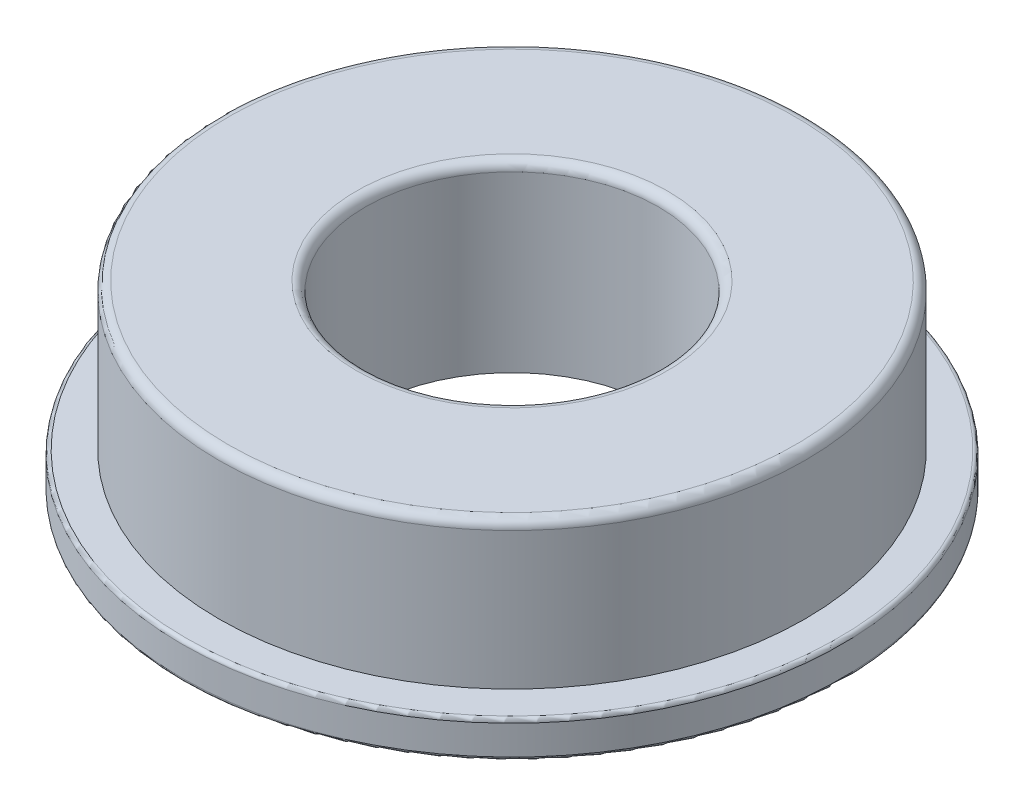
SolidWorks part; units mm, degrees
material "3.0205 (EN-AW 1200)"
ref_plane "Alzado" through (0, 0, 0) normal (0, 0, 1) x (1, 0, 0)
ref_plane "Planta" through (0, 0, 0) normal (0, 1, 0) x (1, 0, 0)
ref_plane "Vista lateral" through (0, 0, 0) normal (1, 0, 0) x (0, 0, -1)
ref_plane "Plano1" through (0, 0, 0) normal (0, 0, -1) x (-1, 0, 0)
sketch "Croquis4" plane through (0, 0, 0) normal (0, 1, 0) x (1, 0, 0)
  circle A0 centre (0, 0) radius 9
sketch "Croquis7" plane through (0, 0, 0) normal (0, 1, 0) x (1, 0, 0)
  circle A0 centre (0, 0) radius 8
sketch "Croquis10" plane through (0, 0, 0) normal (0, 1, 0) x (1, 0, 0)
  circle A0 centre (0, 0) radius 4
extrude "Saliente-Extruir3" add sketch "Croquis7" along normal blind 5 contours A0
extrude "Saliente-Extruir4" add sketch "Croquis4" along normal blind 1
extrude "Cortar-Extruir2" cut sketch "Croquis10" along normal blind 5
fillet "Redondeo1" radius 0.25 2 edges at (0, 5, 4) (0, 5, 8)
fillet "Redondeo2" radius 0.1 2 edges at (0, 1, 9) (0, 0, 9)
